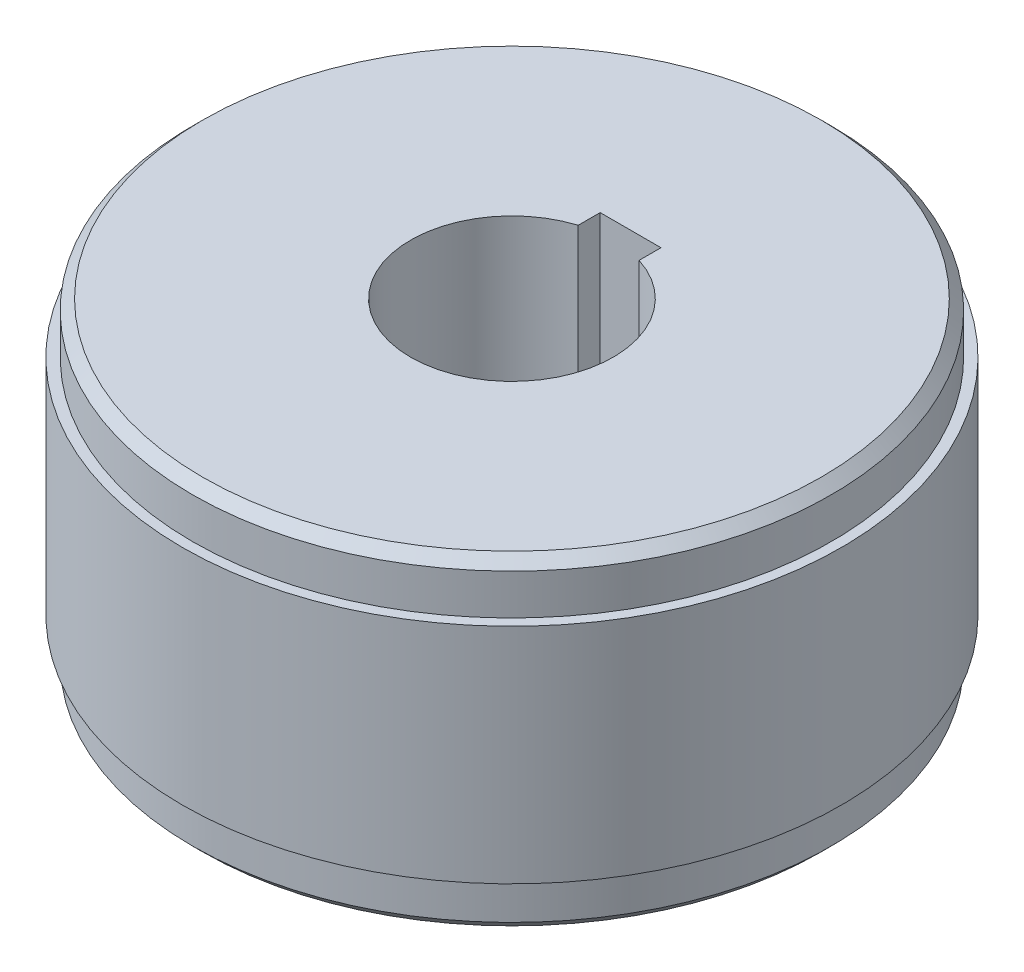
SolidWorks part; units mm, degrees
ref_plane "前视基准面" through (0, 0, 0) normal (0, 0, 1) x (1, 0, 0)
ref_plane "上视基准面" through (0, 0, 0) normal (0, 1, 0) x (1, 0, 0)
ref_plane "右视基准面" through (0, 0, 0) normal (1, 0, 0) x (0, 0, -1)
other "Configuration Table"
sketch "草图1" plane through (0, 0, 0) normal (0, 1, 0) x (1, 0, 0)
  line L0 (0, 67.9563) -> (0, -89.9273) construction
  line L1 (-3, 9.5394) -> (-3, 11.7)
  line L2 (-3, 11.7) -> (3, 11.7)
  line L3 (3, 11.7) -> (3, 9.5394)
  circle A0 centre (0, 0) radius 31.5
  arc A2 (-3, 9.5394) -> (3, 9.5394) centre (0, 0) ccw
  dimension "D1" = 6
  dimension "D3" = 63
  dimension "D2" = 11.7
extrude "凸台-拉伸1" add sketch "草图1" along normal mid plane 32
sketch "草图2" plane through (0, 0, 0) normal (0, 1, 0) x (1, 0, 0)
  circle A0 centre (0, 0) radius 32.5
  circle A1 centre (0, 0) radius 31.5
  dimension "D1" = 65
extrude "凸台-拉伸2" add sketch "草图2" along normal mid plane 22
chamfer "倒角1" distance 1 angle 45 2 edges at (0, 16, 31.5) (0, -16, 31.5)
